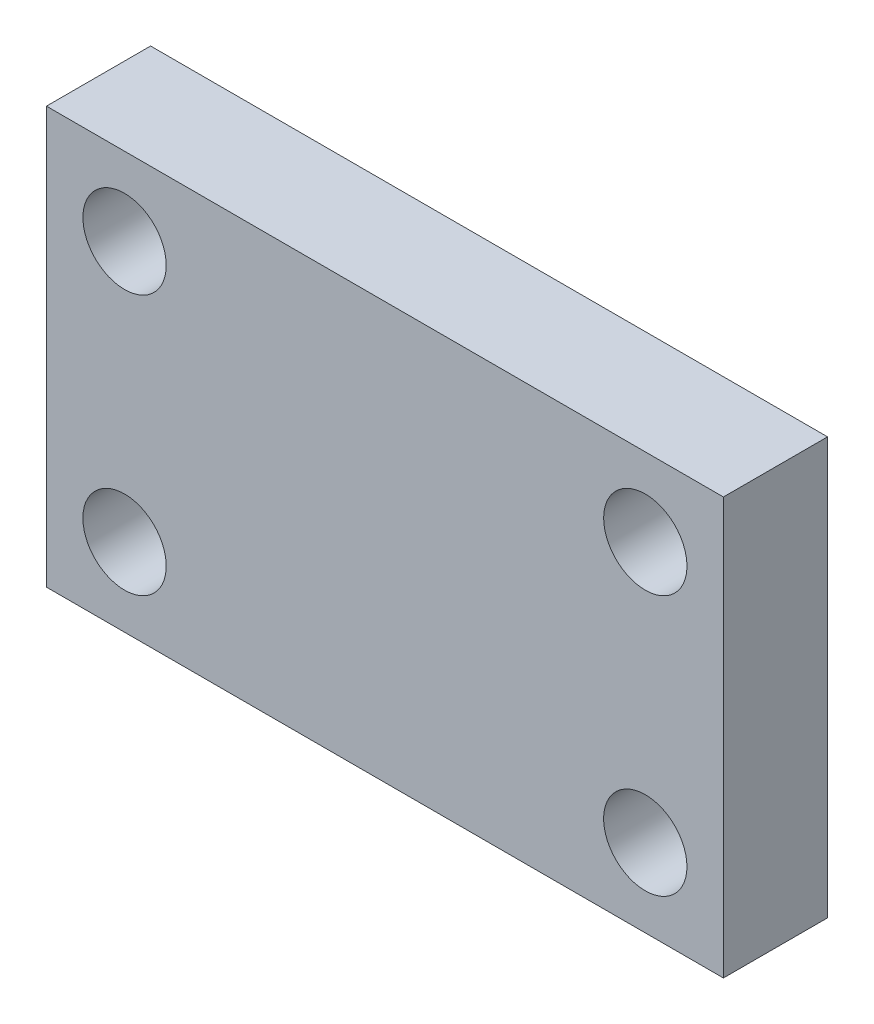
SolidWorks part; units mm, degrees
ref_plane "Plano frontal" through (0, 0, 0) normal (0, 0, 1) x (1, 0, 0)
ref_plane "Plano superior" through (0, 0, 0) normal (0, 1, 0) x (1, 0, 0)
ref_plane "Plano direito" through (0, 0, 0) normal (1, 0, 0) x (0, 0, -1)
sketch "Esboço2" plane through (0, 0, 0) normal (0, 0, 1) x (1, 0, 0)
  line L0 (-75.7368, 0) -> (77.9874, 0) construction
  line L1 (-65, -40) -> (65, -40)
  line L2 (-65, -40) -> (-65, 40)
  line L3 (-65, 40) -> (65, 40)
  line L4 (65, -40) -> (65, 40)
  line L5 (-65, -40) -> (65, 40) construction
  line L6 (-65, 40) -> (65, -40) construction
  line L7 (0, 53.217) -> (0, -55.896) construction
  circle A0 centre (-50, 25) radius 8
  circle A1 centre (50, 25) radius 8
  circle A2 centre (50, -25) radius 8
  circle A3 centre (-50, -25) radius 8
  point P0 (0, 0)
  point P18 (0, 0)
  point P19 (0, 0)
  dimension "D3" = 16
  dimension "D1" = 130
  dimension "D2" = 80
  dimension "D4" = 15
  dimension "D5" = 15
extrude "Ressalto-extrusão1" add sketch "Esboço2" along normal blind 20
